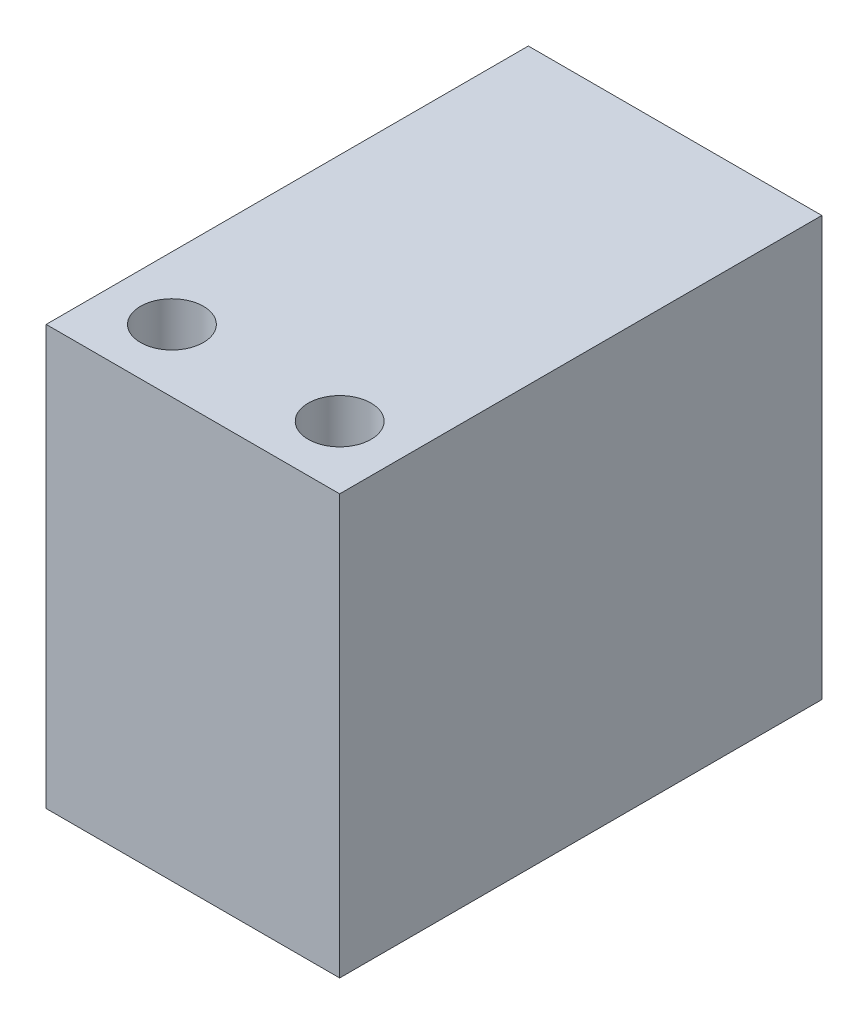
SolidWorks part; units mm, degrees
material "MC nylon"
ref_plane "Front Plane" through (0, 0, 0) normal (0, 0, 1) x (1, 0, 0)
ref_plane "Top Plane" through (0, 0, 0) normal (0, 1, 0) x (1, 0, 0)
ref_plane "Right Plane" through (0, 0, 0) normal (1, 0, 0) x (0, 0, -1)
sketch "Sketch1" plane through (0, 0, 0) normal (0, 1, 0) x (1, 0, 0)
  line L1 (0, 0) -> (14, 0)
  line L2 (0, 0) -> (0, 23)
  line L3 (0, 23) -> (14, 23)
  line L4 (14, 0) -> (14, 23)
  dimension "D1" = 14
  dimension "D2" = 23
extrude "Boss-Extrude1" add sketch "Sketch1" against normal blind 20
hole_wizard "Ø3.0mm Dowel Hole1" positions "Sketch4" profile "Sketch5" hole size "Ø3.0" standard "JIS"
sketch "Sketch4" plane through (0, 0, 0) normal (0, 1, 0) x (1, 0, 0)
  line L0 (0, 23) -> (0, 0) construction
  line L1 (0, 0) -> (14, 0) construction
  point P0 (3, 3)
  point P2 (11, 3)
  dimension "D1" = 8
  dimension "D2" = 3
  dimension "D3" = 3
sketch "Sketch5" plane through (3, 0, -3) normal (1, 0, 0) x (0, 0, 1)
  line L0 (0, 0) -> (0, 5.9013)
  line L1 (0, 5.9013) -> (1.5, 5)
  line L2 (1.5, 5) -> (1.5, 0)
  line L5 (1.5, 0) -> (0, 0)
  line L10 (0, 5.9013) -> (-1.5, 5) construction
  line L11 (0, -6.35) -> (0, 107.95) construction
  dimension "Hole Dia." = 3
  dimension "Hole Depth" = 5
  dimension "Drill Angle" = 118
hole_wizard "M10x1.0 Tapped Hole1" positions "Sketch6" profile "Sketch7" tap size "M10x1.0" standard "JIS"
sketch "Sketch6" plane through (0, -20, 0) normal (0, -1, 0) x (-1, 0, 0)
  line L0 (-14, 23) -> (0, 23) construction
  line L1 (-14, 0) -> (-14, 23) construction
  point P0 (-7, 15)
  dimension "D1" = 8
  dimension "D2" = 7
sketch "Sketch7" plane through (7, -20, -15) normal (1, 0, 0) x (0, 0, -1)
  line L0 (0, 0) -> (0, 14.7039)
  line L1 (0, 14.7039) -> (4.5, 12)
  line L2 (4.5, 12) -> (4.5, 0)
  line L5 (4.5, 0) -> (0, 0)
  line L10 (0, 14.7039) -> (-4.5, 12) construction
  line L11 (0, -6.35) -> (0, 107.95) construction
  dimension "Tap Drill Dia." = 9
  dimension "Tap Drill Depth" = 12
  dimension "Drill Angle" = 118
cosmetic thread "Hole Thread1"
